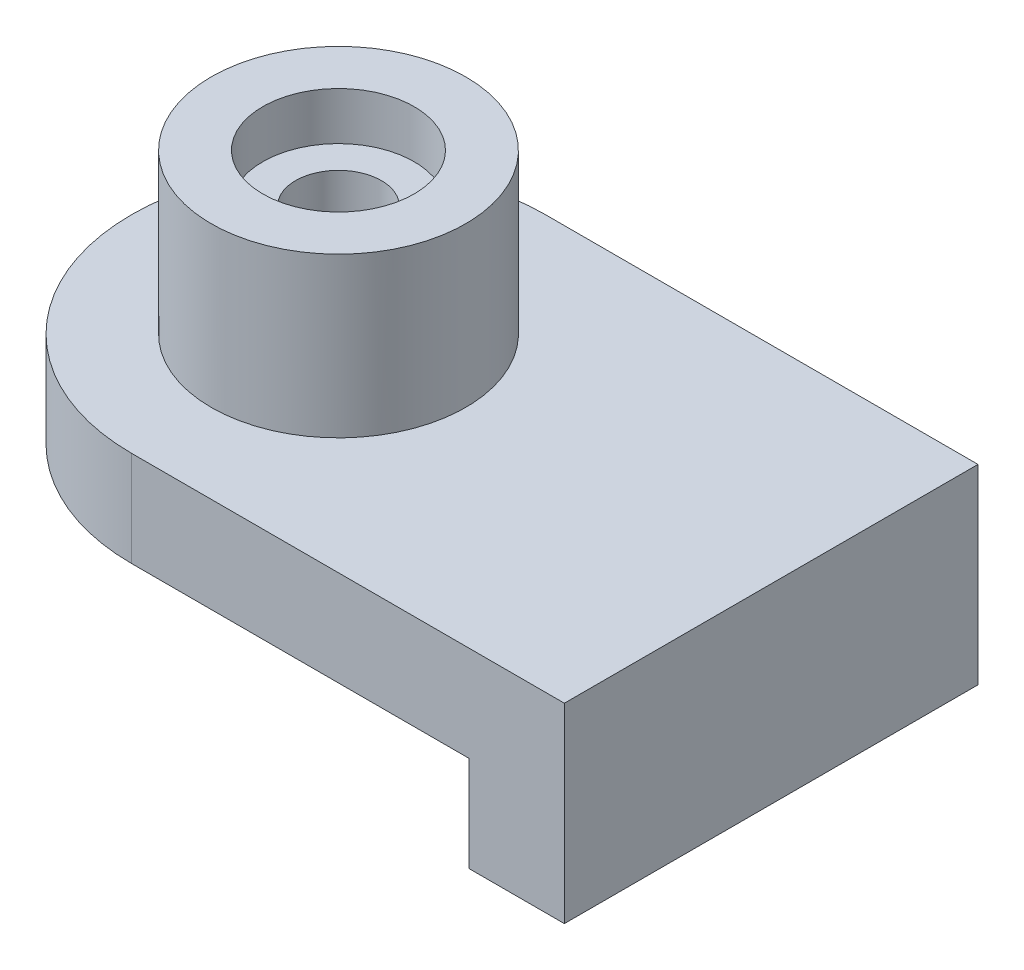
SolidWorks part; units mm, degrees
material "2014 Alloy"
ref_plane "Front Plane" through (0, 0, 0) normal (0, 0, 1) x (1, 0, 0)
ref_plane "Top Plane" through (0, 0, 0) normal (0, 1, 0) x (1, 0, 0)
ref_plane "Right Plane" through (0, 0, 0) normal (1, 0, 0) x (0, 0, -1)
sketch "Sketch1" plane through (0, 0, 0) normal (0, 0, 1) x (1, 0, 0)
  line L0 (0, 0) -> (0, 15)
  line L1 (0, 15) -> (68, 15)
  line L2 (68, 15) -> (68, -15)
  line L3 (68, -15) -> (53, -15)
  line L4 (53, -15) -> (53, 0)
  line L5 (53, 0) -> (0, 0)
  dimension "D1" = 30
  dimension "D2" = 15
  dimension "D3" = 15
  dimension "D4" = 68
extrude "Boss-Extrude1" add sketch "Sketch1" along normal blind 65
sketch "Sketch2" plane through (0, 15, 0) normal (0, 1, 0) x (1, 0, 0)
  line L0 (0, -65) -> (0, 0) construction
  circle A0 centre (0, -32.5) radius 32.5
extrude "Boss-Extrude2" add sketch "Sketch2" against normal up to vertex
sketch "Sketch3" plane through (0, 15, 0) normal (0, 1, 0) x (1, 0, 0)
  circle A0 centre (0, -32.5) radius 20
  dimension "D1" = 40
extrude "Boss-Extrude4" add sketch "Sketch3" along direction (0, -1, 0) on the side of the normal offset from surface (25 mm away) 55
hole_wizard "CBORE for #1 Binding Head Machine Screw1" positions "Sketch4" profile "Sketch6" counterbore size "#1" standard "ANSI Inch" end condition up to next
sketch "Sketch4" plane through (0, 40, 0) normal (0, 1, 0) x (1, 0, 0)
  point P0 (0, -32.5)
sketch "Sketch6" plane through (0, 40, 32.5) normal (1, 0, 0) x (0, 0, 1)
  line L0 (0, 0) -> (0, 40)
  line L1 (0, 40) -> (6.75, 40)
  line L3 (6.75, 40) -> (6.75, 7.5)
  line L4 (6.75, 7.5) -> (11.895, 7.5)
  line L5 (11.895, 7.5) -> (11.895, 0)
  line L7 (11.895, 0) -> (0, 0)
  line L11 (0, -6.35) -> (0, 107.95) construction
  dimension "Thru Hole Dia." = 13.5
  dimension "Thru Hole Depth" = 40
  dimension "C'Bore Dia." = 23.79
  dimension "C'Bore Depth" = 7.5
